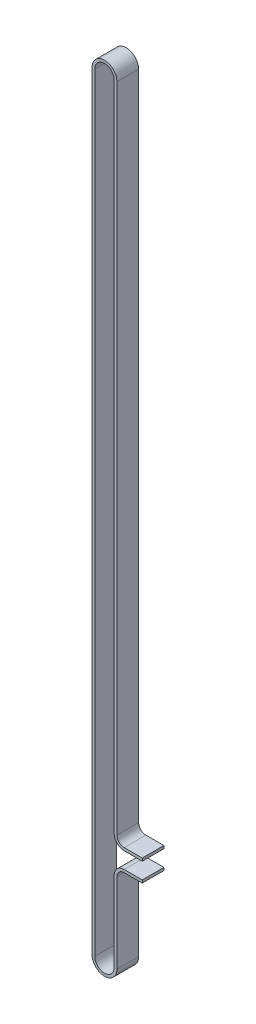
SolidWorks part; units mm, degrees
ref_plane "Front Plane" through (0, 0, 0) normal (0, 0, 1) x (1, 0, 0)
ref_plane "Top Plane" through (0, 0, 0) normal (0, 1, 0) x (1, 0, 0)
ref_plane "Right Plane" through (0, 0, 0) normal (1, 0, 0) x (0, 0, -1)
sketch "Sketch1" plane through (0, 0, 0) normal (0, 0, 1) x (1, 0, 0)
  line L0 (-6.365, 0) -> (-6.365, -425)
  line L2 (6.365, -425) -> (6.365, -380.8)
  line L3 (6.881, -425) -> (6.881, -380.8) construction
  line L4 (6.365, -360.8) -> (6.365, 0)
  line L5 (10.881, -365.316) -> (20.881, -365.316)
  line L6 (20.881, -364.8) -> (10.881, -364.8) construction
  line L7 (6.881, -360.8) -> (6.881, 0) construction
  line L8 (10.881, -376.8) -> (20.881, -376.8) construction
  line L9 (10.881, -376.284) -> (20.881, -376.284)
  arc A0 (6.365, 0) -> (-6.365, 0) centre (0, 0) ccw
  arc A1 (-6.365, -425) -> (6.365, -425) centre (0, -425) ccw
  arc A2 (10.881, -364.8) -> (6.881, -360.8) centre (10.881, -360.8) cw construction
  arc A3 (10.881, -365.316) -> (6.365, -360.8) centre (10.881, -360.8) cw
  arc A4 (10.881, -365.316) -> (6.365, -360.8) centre (10.881, -360.8) cw construction
  arc A5 (6.881, -380.8) -> (10.881, -376.8) centre (10.881, -380.8) cw construction
  arc A6 (6.365, -380.8) -> (10.881, -376.284) centre (10.881, -380.8) cw
  arc A7 (6.365, -380.8) -> (10.881, -376.284) centre (10.881, -380.8) cw construction
  point P24 (0, 0)
  point P27 (0, 0)
  point P28 (0, 0)
  dimension "D1" = 12.73
  dimension "D3" = 0.516
  dimension "D7" = 4
  dimension "D5" = 4
  dimension "D2" = 425
  dimension "D4" = 0.516
  dimension "D6" = 10
  dimension "D8" = 0.516
  dimension "D9" = 10
  dimension "D10" = 12
  dimension "D11" = 48.2
extrude "Extrude-Thin1" add sketch "Sketch1" along normal blind 12 thin thin type two direction wall 1.004 second wall 0.516
